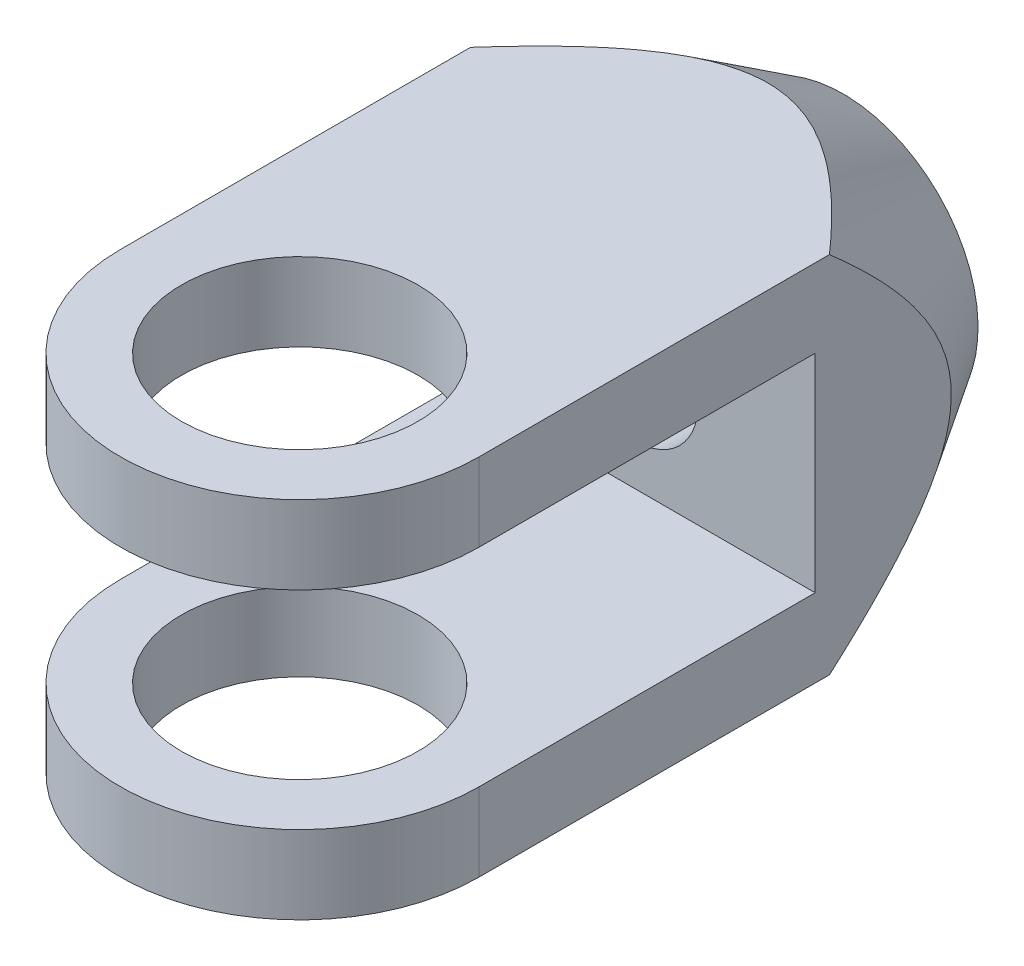
SolidWorks part; units mm, degrees
ref_plane "Front Plane" through (0, 0, 0) normal (0, 0, 1) x (1, 0, 0)
ref_plane "Top Plane" through (0, 0, 0) normal (0, 1, 0) x (1, 0, 0)
ref_plane "Right Plane" through (0, 0, 0) normal (1, 0, 0) x (0, 0, -1)
sketch "Sketch1" plane through (0, 0, 0) normal (0, 1, 0) x (1, 0, 0)
  line L0 (-997.2213, -10.9855) -> (49002.7787, -10.9855) construction
  line L2 (-10.9855, 0) -> (-10.9855, 33.2613)
  line L3 (-10.9855, 33.2613) -> (10.9855, 33.2613)
  line L4 (10.9855, 0) -> (10.9855, 33.2613)
  circle A0 centre (0, 0) radius 7.239
  arc A1 (-10.9855, 0) -> (10.9855, 0) centre (0, 0) ccw
  dimension "D1" = 14.478
  dimension "D2" = 21.971
  dimension "D3" = 44.2468
extrude "Boss-Extrude1" add sketch "Sketch1" along normal blind 22.2758
sketch "Sketch2" plane through (0, 0, 0) normal (1, 0, 0) x (0, 0, -1)
  line L0 (-10.9855, 22.2758) -> (-10.9855, 0) construction
  line L1 (-10.9855, 17.4879) -> (20.5613, 17.4879)
  line L2 (-10.9855, 17.4879) -> (-10.9855, 4.7879)
  line L3 (-10.9855, 4.7879) -> (20.5613, 4.7879)
  line L4 (20.5613, 17.4879) -> (20.5613, 4.7879)
  line L5 (33.2613, 11.1379) -> (-10.9855, 11.1379) construction
  line L6 (33.2613, 22.2758) -> (33.2613, 0) construction
  dimension "D1" = 12.7
  dimension "D2" = 6.35
  dimension "D3" = 12.7
extrude "Cut-Extrude1" cut sketch "Sketch2" against normal mid plane 25.4
sketch "Sketch3" plane through (0, 0, -33.2613) normal (0, 0, -1) x (-1, 0, 0)
  line L0 (-10.9855, 22.2758) -> (10.9855, 0) construction
  line L1 (10.9855, 22.2758) -> (-10.9855, 0) construction
  circle A0 centre (0, 11.1379) radius 8.255 construction
  dimension "D1" = 16.51
ref_plane "Plane1" through (5.5684, 5.4922, 0) normal (-0.712, -0.7022, 0) x (0, 0, 1)
sketch "Sketch5" plane through (5.5684, 5.4922, 0) normal (-0.712, -0.7022, 0) x (0, 0, 1)
  line L0 (-21.4365, 23.5737) -> (-33.2613, 16.1847)
  line L1 (-33.2613, 23.5737) -> (0, 23.5737) construction
  line L2 (-33.2613, 16.1847) -> (-33.2613, -0.3253) construction
  line L3 (-33.2613, 16.1847) -> (-33.2613, 23.5737)
  line L4 (-33.2613, 23.5737) -> (-21.4365, 23.5737)
  dimension "D1" = 32
sketch "Sketch6" plane through (5.5684, 5.4922, 0) normal (-0.712, -0.7022, 0) x (0, 0, 1)
  line L0 (-33.2613, 7.9297) -> (11.4185, 7.9297) construction
revolve "Cut-Revolve1" cut sketch "Sketch5" angle 360 about L0
sketch "Sketch7" plane through (0, 0, -33.2613) normal (0, 0, -1) x (-1, 0, 0)
  line L0 (10.9855, 22.2758) -> (-10.9855, 0) construction
  circle A0 centre (0, 11.1379) radius 3.81
  dimension "D1" = 7.62
extrude "Cut-Extrude2" cut sketch "Sketch7" against normal up to next
